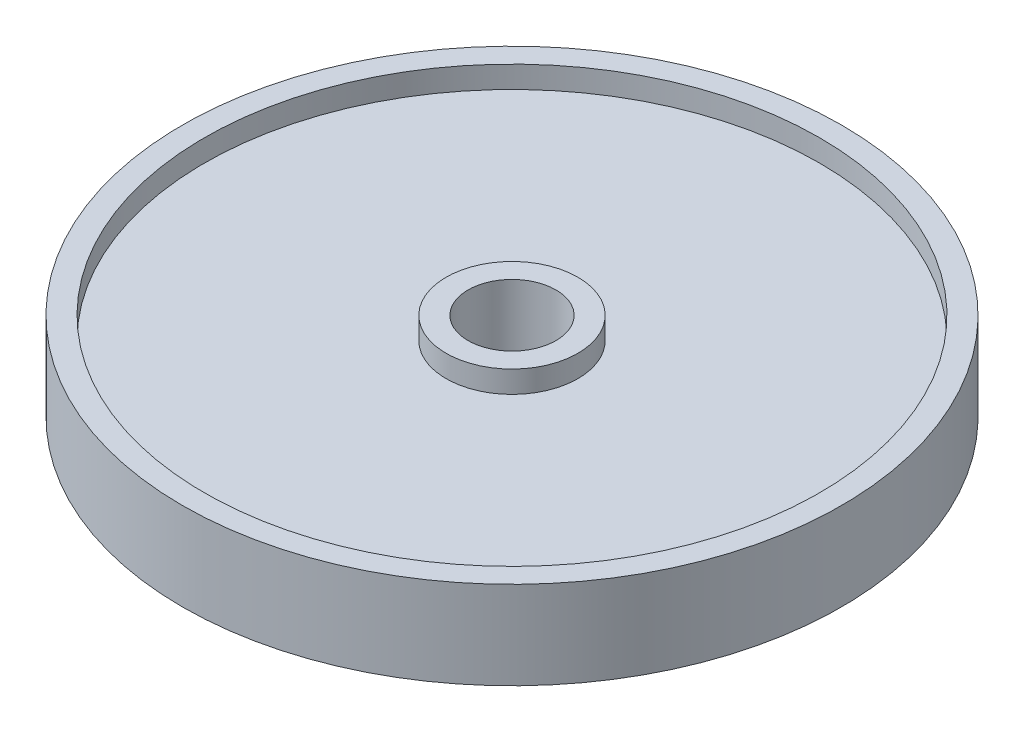
SolidWorks part; units mm, degrees
ref_plane "Front" through (0, 0, 0) normal (0, 0, 1) x (1, 0, 0)
ref_plane "Top" through (0, 0, 0) normal (0, 1, 0) x (1, 0, 0)
ref_plane "Right" through (0, 0, 0) normal (1, 0, 0) x (0, 0, -1)
sketch "Sketch1" plane through (0, 0, 0) normal (0, 0, 1) x (1, 0, 0)
  line L0 (0, -9.4822) -> (0, 10.4805) construction
  line L1 (5, -17.5) -> (5, 17.5) construction
  line L2 (5, 5) -> (7.5, 5)
  line L3 (5, 5) -> (5, -5)
  line L4 (5, -5) -> (7.5, -5)
  line L5 (37.5, 5) -> (37.5, -5)
  line L6 (7.5, 2.5) -> (35, 2.5)
  line L7 (35, 5) -> (35, 2.5)
  line L8 (7.5, -2.5) -> (35, -2.5)
  line L9 (7.5, 5) -> (7.5, 2.5)
  line L10 (35, 5) -> (37.5, 5)
  line L11 (35, -5) -> (37.5, -5)
  line L12 (35, -2.5) -> (35, -5)
  line L13 (7.5, -2.5) -> (7.5, -5)
  point P9 (5, 0)
  dimension "D1" = 10
  dimension "D2" = 75
  dimension "D3" = 2.5
revolve "Revolve1" add sketch "Sketch1" angle 360 about L0
